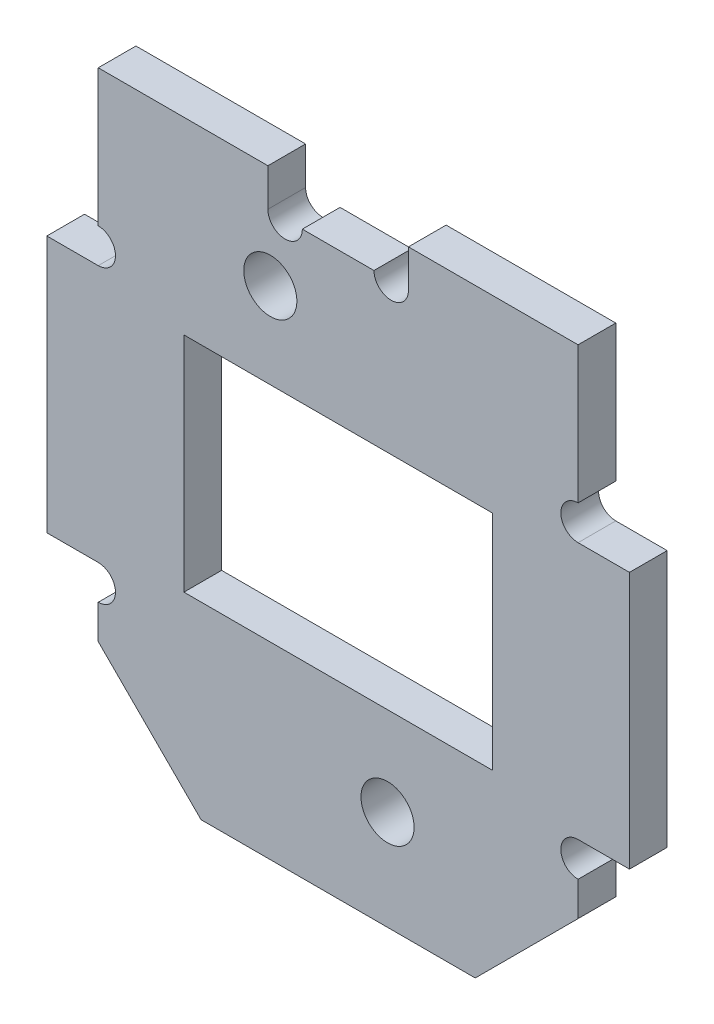
SolidWorks part; units mm, degrees
material "Thornel Mat VMA"
ref_plane "前视基准面" through (0, 0, 0) normal (0, 0, 1) x (1, 0, 0)
ref_plane "上视基准面" through (0, 0, 0) normal (0, 1, 0) x (1, 0, 0)
ref_plane "右视基准面" through (0, 0, 0) normal (1, 0, 0) x (0, 0, -1)
sketch "草图1" plane through (0, 0, 0) normal (0, 0, 1) x (1, 0, 0)
  line L0 (-3.958, 11.5) -> (5.9447, 10.1083) construction
  line L1 (14, -17.5) -> (-14, -17.5)
  line L2 (14, -17.5) -> (14, -7.5)
  line L3 (14, 17.5) -> (4.1, 17.5)
  line L4 (-14, -17.5) -> (-14, -7.5)
  line L5 (14, -17.5) -> (-14, 17.5) construction
  line L6 (14, 17.5) -> (-14, -17.5) construction
  line L7 (5.9447, 10.1083) -> (2.8828, -11.6776) construction
  line L8 (-14, 7.5) -> (-17, 7.5)
  line L9 (-17, 7.5) -> (-17, -7.5)
  line L10 (-17, -7.5) -> (-14, -7.5)
  line L11 (-4.1, 17.5) -> (-4.1, 15.3)
  line L12 (-4.1, 15.3) -> (4.1, 15.3)
  line L13 (4.1, 15.3) -> (4.1, 17.5)
  line L14 (0, 15.3) -> (0, 12.1066) construction
  line L15 (-4.1, 17.5) -> (-14, 17.5)
  line L16 (-17, 0) -> (-7.1439, 0) construction
  line L17 (-14, 7.5) -> (-14, 17.5)
  line L18 (0, 0) -> (0, 7.5) construction
  line L22 (14, 7.5) -> (14, 17.5)
  line L23 (0.9933, 10.8041) -> (-0.5922, -0.4774) construction
  line L25 (17, -7.5) -> (14, -7.5)
  line L26 (17, 7.5) -> (17, -7.5)
  line L27 (14, 7.5) -> (17, 7.5)
  line L29 (9, -6.5) -> (-9, -6.5)
  line L30 (9, -6.5) -> (9, 6.5)
  line L31 (9, 6.5) -> (-9, 6.5)
  line L32 (-9, -6.5) -> (-9, 6.5)
  line L33 (9, -6.5) -> (-9, 6.5) construction
  line L34 (9, 6.5) -> (-9, -6.5) construction
  circle A0 centre (-3.958, 11.5) radius 1.55
  circle A1 centre (2.8828, -11.6776) radius 1.55
  circle A2 centre (-3.095, 15.3) radius 1.005
  circle A3 centre (3.095, 15.3) radius 1.005
  circle A4 centre (-14, 8.505) radius 1.005
  circle A5 centre (-14, -8.505) radius 1.005
  circle A6 centre (14, -8.505) radius 1.005
  circle A7 centre (14, 8.505) radius 1.005
  point P0 (0, 0)
  point P19 (-4.1, 16.4)
  dimension "D4" = 3.1
  dimension "D13" = 2.01
  dimension "D1" = 8
  dimension "D2" = 10
  dimension "D3" = 22
  dimension "D5" = 14
  dimension "D6" = 6
  dimension "D7" = 35
  dimension "D8" = 0.52
  dimension "D9" = 3
  dimension "D10" = 15
  dimension "D11" = 2.2
  dimension "D12" = 8.2
  dimension "D14" = 5
  dimension "D15" = 18
extrude "凸台-拉伸1" add sketch "草图1" along normal blind 2.2
chamfer "倒角1" distance 6 angle 45 2 edges at (14, -17.5, 1.1) (-14, -17.5, 1.1)
